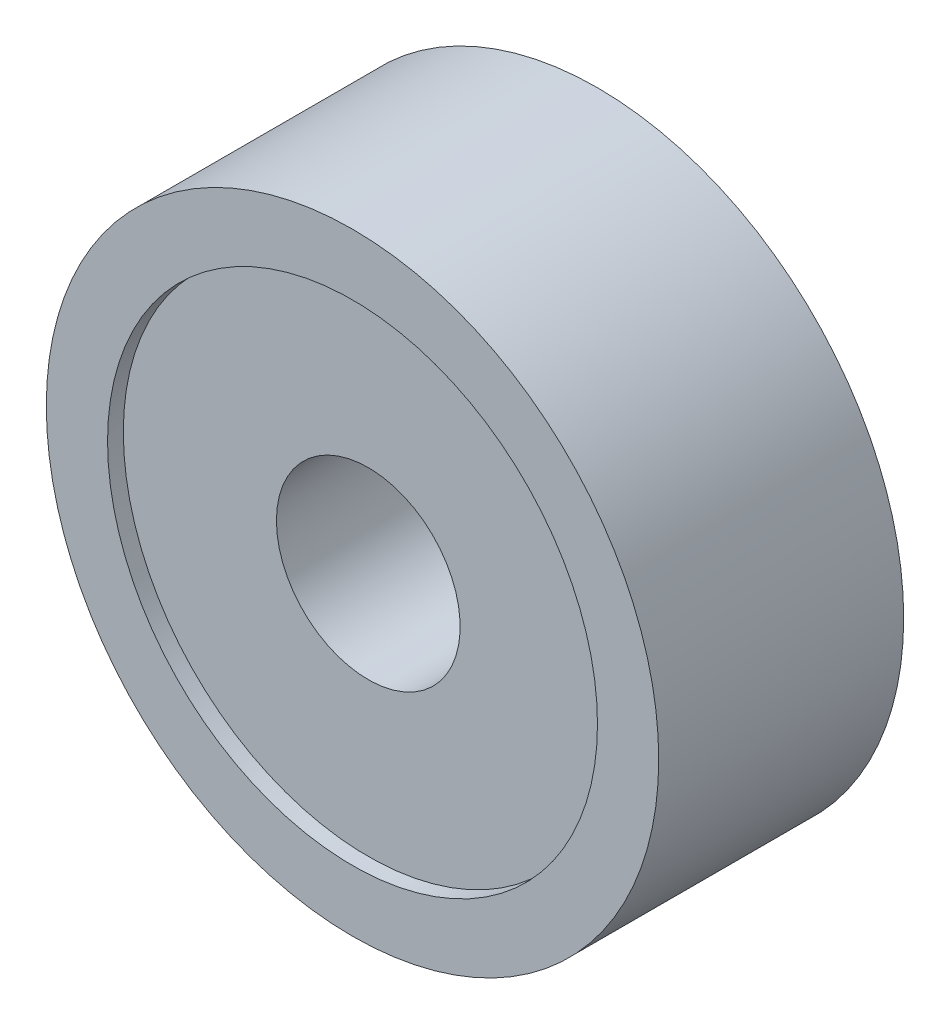
SolidWorks part; units mm, degrees
ref_plane "Front Plane" through (0, 0, 0) normal (0, 0, 1) x (1, 0, 0)
ref_plane "Top Plane" through (0, 0, 0) normal (0, 1, 0) x (1, 0, 0)
ref_plane "Right Plane" through (0, 0, 0) normal (1, 0, 0) x (0, 0, -1)
sketch "Sketch2" plane through (0, 0, 0) normal (0, 0, 1) x (1, 0, 0)
  circle A0 centre (0, 0) radius 5
  circle A1 centre (0, 0) radius 1.5
  dimension "D1" = 10
  dimension "D2" = 3
extrude "Boss-Extrude1" add sketch "Sketch2" along normal blind 4
sketch "Sketch3" plane through (0, 0, 0) normal (0, 1, 0) x (1, 0, 0)
  line L0 (5, 0) -> (-5, 0) construction
  line L1 (-1, 0.25) -> (-4, 0.25)
  line L2 (-1, 0.25) -> (-1, -0.25)
  line L3 (-1, -0.25) -> (-4, -0.25)
  line L4 (-4, 0.25) -> (-4, -0.25)
  line L5 (-1, 0.25) -> (-4, -0.25) construction
  line L6 (-1, -0.25) -> (-4, 0.25) construction
  line L7 (-5, 0) -> (-5, -4) construction
  line L8 (0, 0) -> (0, -3.9925) construction
  line L9 (-5.8554, -1.9963) -> (6.0606, -1.9963) construction
  line L10 (-1, -3.7425) -> (-4, -3.7425)
  line L11 (-4, -4.2425) -> (-4, -3.7425)
  line L12 (-1, -4.2425) -> (-4, -4.2425)
  line L13 (-1, -4.2425) -> (-1, -3.7425)
  point P0 (-2.5, 0)
  dimension "D1" = 1
  dimension "D2" = 1
  dimension "D3" = 0.5
revolve "Cut-Revolve1" cut sketch "Sketch3" angle 360 about L8
